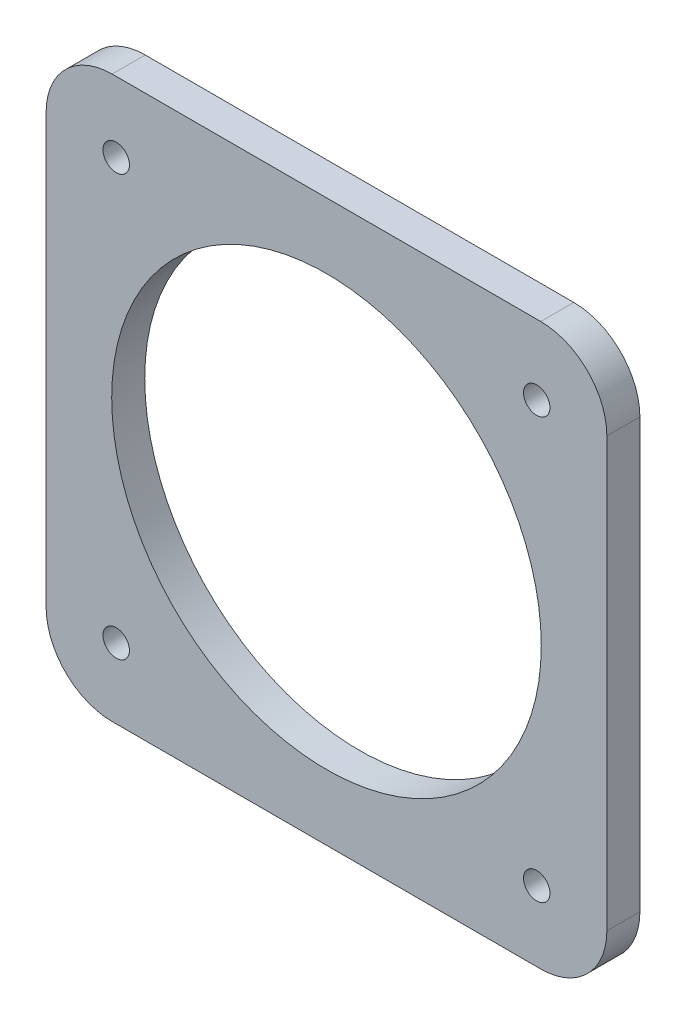
SolidWorks part; units mm, degrees
ref_plane "Front Plane" through (0, 0, 0) normal (0, 0, 1) x (1, 0, 0)
ref_plane "Top Plane" through (0, 0, 0) normal (0, 1, 0) x (1, 0, 0)
ref_plane "Right Plane" through (0, 0, 0) normal (1, 0, 0) x (0, 0, -1)
sketch "Sketch1" plane through (0, 0, 0) normal (0, 0, 1) x (1, 0, 0)
  line L1 (-5.5355, 65.4307) -> (59.3145, 65.4307)
  line L2 (-15.5355, 55.4307) -> (-15.5355, -9.4193)
  line L3 (-5.5355, -19.4193) -> (59.3145, -19.4193)
  line L4 (69.3145, 55.4307) -> (69.3145, -9.4193)
  circle A0 centre (26.8895, 23.0057) radius 32.5
  arc A1 (59.3145, 65.4307) -> (69.3145, 55.4307) centre (59.3145, 55.4307) cw
  arc A2 (59.3145, -19.4193) -> (69.3145, -9.4193) centre (59.3145, -9.4193) ccw
  arc A3 (-15.5355, -9.4193) -> (-5.5355, -19.4193) centre (-5.5355, -9.4193) ccw
  arc A4 (-5.5355, 65.4307) -> (-15.5355, 55.4307) centre (-5.5355, 55.4307) ccw
  circle A5 centre (-4.9255, 54.8207) radius 2
  circle A6 centre (-4.9255, -8.8093) radius 2
  circle A7 centre (58.7045, 54.8207) radius 2
  circle A8 centre (58.7045, -8.8093) radius 2
  dimension "D1" = 10
  dimension "D2" = 10
  dimension "D3" = 10
  dimension "D4" = 10
  dimension "D5" = 65
extrude "Boss-Extrude2" add sketch "Sketch1" along normal blind 5
